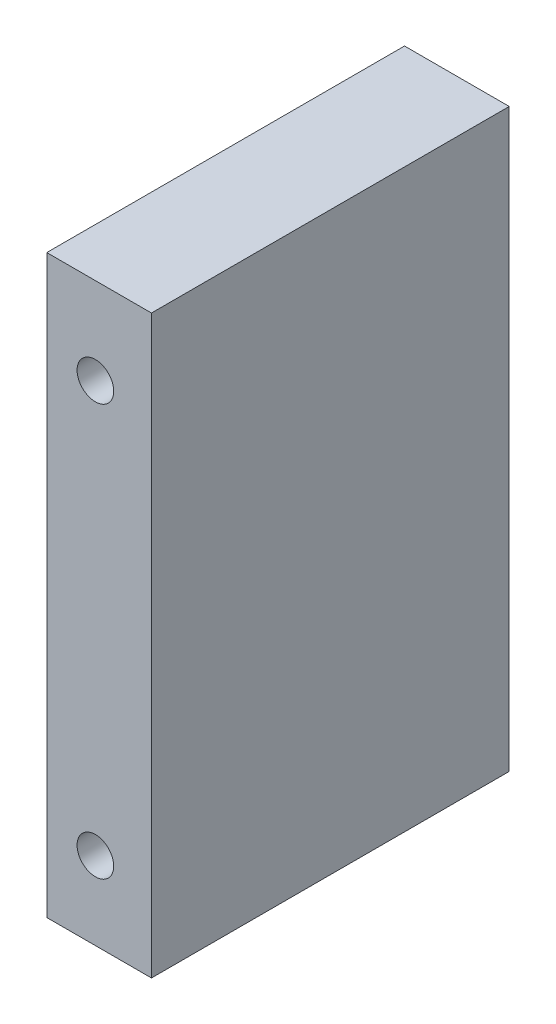
SolidWorks part; units mm, degrees
material "1.0037 (S235JR)"
ref_plane "Płaszczyzna przednia" through (0, 0, 0) normal (0, 0, 1) x (1, 0, 0)
ref_plane "Płaszczyzna górna" through (0, 0, 0) normal (0, 1, 0) x (1, 0, 0)
ref_plane "Płaszczyzna prawa" through (0, 0, 0) normal (1, 0, 0) x (0, 0, -1)
sketch "Szkic1" plane through (0, 0, 0) normal (0, 0, 1) x (1, 0, 0)
  line L0 (-46, -55) -> (-46, 11) construction
  line L1 (-52, -55) -> (-40, -55)
  line L2 (-52, -55) -> (-52, 11)
  line L3 (-52, 11) -> (-40, 11)
  line L4 (-40, -55) -> (-40, 11)
  line L5 (0, -67) -> (0, 13) construction
  line L7 (0, 13) -> (-140, 13) construction
  dimension "D1" = 12
  dimension "D2" = 46
  dimension "D3" = 66
  dimension "D4" = 2
extrude "Dodanie-wyciągnięcie1" add sketch "Szkic1" along normal blind 41
sketch "Szkic2" plane through (0, 0, 0) normal (0, 0, -1) x (-1, 0, 0)
  line L0 (46, -55) -> (46, 11) construction
  line L1 (52, -55) -> (40, -55) construction
  line L2 (40, 11) -> (52, 11) construction
hole_wizard "Otwór gwintowany M5x0.81" positions "Szkic4" profile "Szkic3" tap size "M5x0.8" standard "Ansi Metric"
sketch "Szkic4" plane through (0, 0, 0) normal (0, 0, -1) x (-1, 0, 0)
  line L0 (46, -55) -> (46, 11) construction
  line L1 (52, -55) -> (40, -55) construction
  line L2 (40, 11) -> (52, 11) construction
  point P0 (46, -39)
  point P4 (46, -5)
  dimension "D1" = 16
  dimension "D2" = 16
sketch "Szkic3" plane through (-46, -39, 0) normal (1, 0, 0) x (0, 1, 0)
  line L0 (0, 0) -> (0, 26.2618)
  line L1 (0, 26.2618) -> (2.1, 25)
  line L2 (2.1, 25) -> (2.1, 0)
  line L5 (2.1, 0) -> (0, 0)
  line L10 (0, 26.2618) -> (-2.1, 25) construction
  line L11 (0, -6.35) -> (0, 107.95) construction
  dimension "Średnica wiertła gwintu" = 4.2
  dimension "Głębokość otworu gwintowanego" = 25
  dimension "Kąt wiertła" = 118
hole_wizard "Otwór gwintowany M5x0.82" positions "Szkic6" profile "Szkic5" tap size "M5x0.8" standard "Ansi Metric"
sketch "Szkic6" plane through (0, 0, 41) normal (0, 0, 1) x (1, 0, 0)
  point P0 (-46.43, -46.07)
  point P3 (-46.43, 1.07)
sketch "Szkic5" plane through (-46.43, -46.07, 41) normal (1, 0, 0) x (0, -1, 0)
  line L0 (0, 0) -> (0, 26.2618)
  line L1 (0, 26.2618) -> (2.1, 25)
  line L2 (2.1, 25) -> (2.1, 0)
  line L5 (2.1, 0) -> (0, 0)
  line L10 (0, 26.2618) -> (-2.1, 25) construction
  line L11 (0, -6.35) -> (0, 107.95) construction
  dimension "Średnica wiertła gwintu" = 4.2
  dimension "Głębokość otworu gwintowanego" = 25
  dimension "Kąt wiertła" = 118
equation "\"D2@Szkic4\"=\"D1@Szkic4\""
